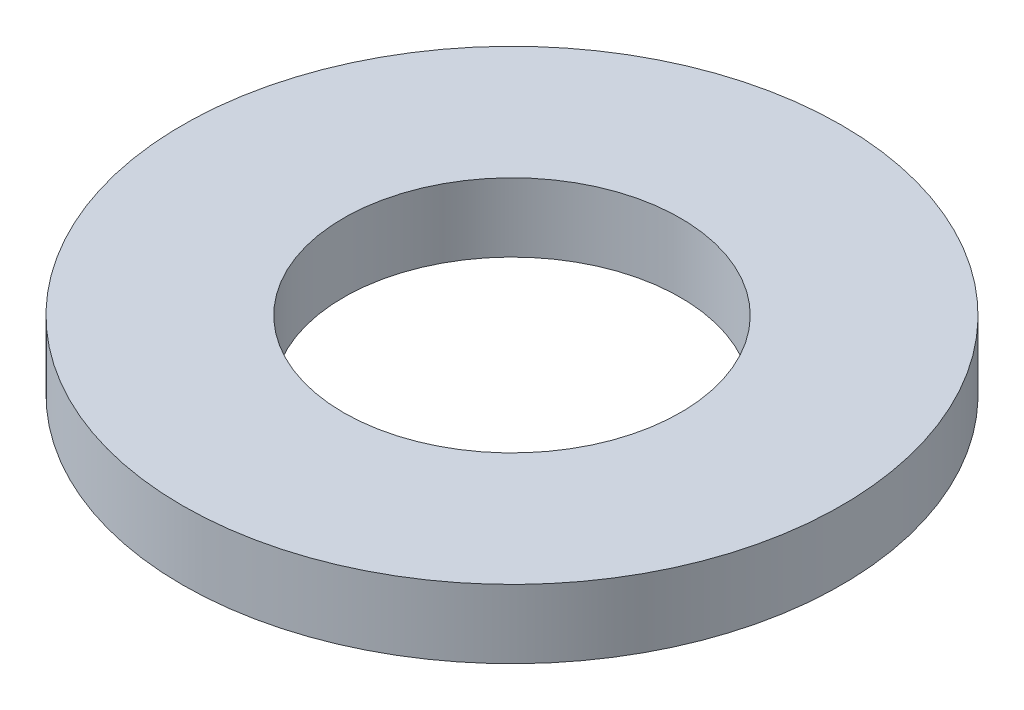
SolidWorks part; units mm, degrees
material "AISI 316 Нержавеющая сталь, лист (SS)"
ref_plane "Спереди" through (0, 0, 0) normal (0, 0, 1) x (1, 0, 0)
ref_plane "Сверху" through (0, 0, 0) normal (0, 1, 0) x (1, 0, 0)
ref_plane "Справа" through (0, 0, 0) normal (1, 0, 0) x (0, 0, -1)
sketch "Эскиз1" plane through (0, 0, 0) normal (0, 1, 0) x (1, 0, 0)
  circle A0 centre (0, 0) radius 6.135
  circle A1 centre (0, 0) radius 12
  dimension "D1" = 12.27
  dimension "D2" = 24
extrude "Бобышка-Вытянуть1" add sketch "Эскиз1" along normal blind 2.5
